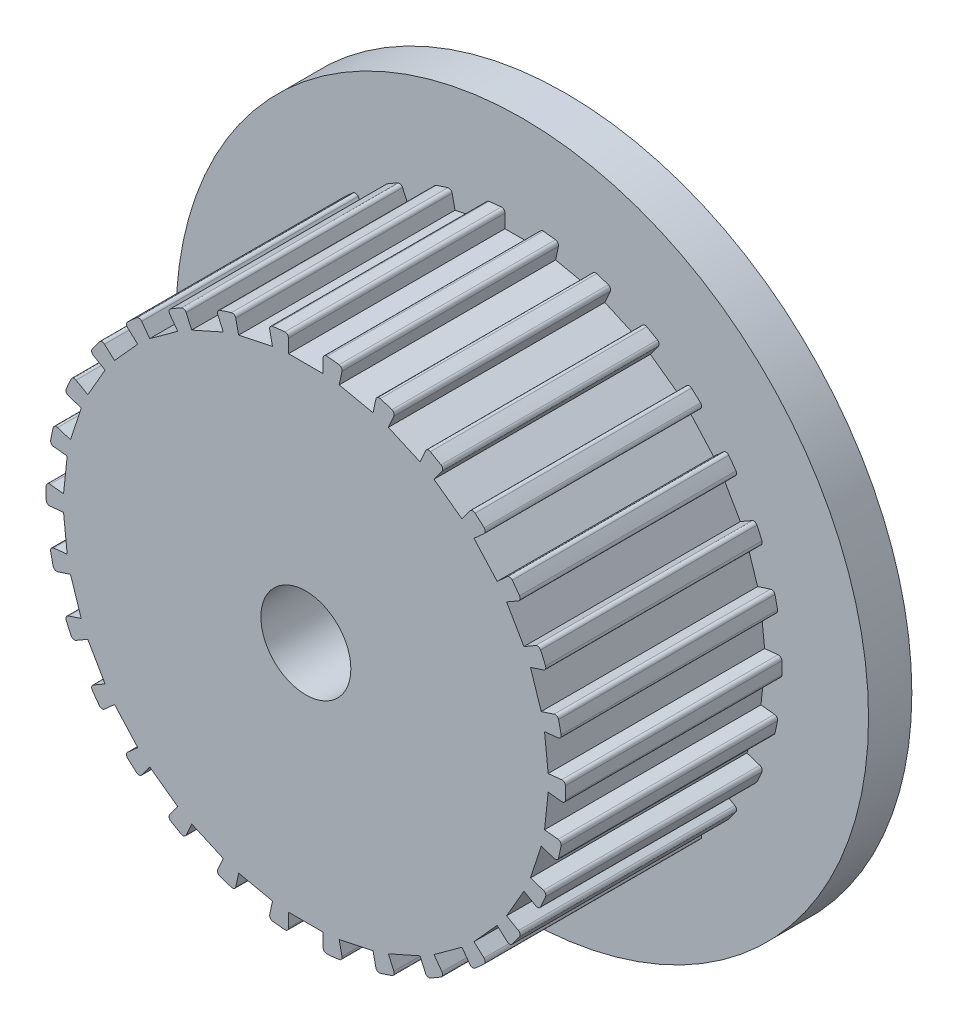
SolidWorks part; units mm, degrees
ref_plane "Front Plane" through (0, 0, 0) normal (0, 0, 1) x (1, 0, 0)
ref_plane "Top Plane" through (0, 0, 0) normal (0, 1, 0) x (1, 0, 0)
ref_plane "Right Plane" through (0, 0, 0) normal (1, 0, 0) x (0, 0, -1)
sketch "Sketch1" plane through (0, 0, 0) normal (0, 0, 1) x (1, 0, 0)
  circle A0 centre (0, 0) radius 12.7
  dimension "D1" = 25.4
extrude "Boss-Extrude1" add sketch "Sketch1" along normal blind 1.5875
sketch "Sketch2" plane through (0, 0, 1.5875) normal (0, 0, 1) x (1, 0, 0)
  circle A0 centre (0, 0) radius 9.525
  dimension "D1" = 19.05
extrude "Boss-Extrude2" add sketch "Sketch2" along normal blind 7.9375
sketch "Sketch3" plane through (0, 0, 9.525) normal (0, 0, 1) x (1, 0, 0)
  circle A0 centre (0, 0) radius 1.65
  dimension "D1" = 3.3
extrude "Cut-Extrude1" cut sketch "Sketch3" against normal through all
sketch "Sketch4" plane through (0, 0, 9.525) normal (0, 0, 1) x (1, 0, 0)
  line L0 (0, 8.8688) -> (0, 9.525) construction
  line L6 (-0.635, 9.5038) -> (0.635, 9.5038)
  line L7 (-0.635, 9.5038) -> (-0.635, 10.1388)
  line L8 (-0.635, 10.1388) -> (0.635, 10.1388)
  line L9 (0.635, 9.5038) -> (0.635, 10.1388)
  line L10 (-0.635, 9.5038) -> (0.635, 9.5038)
  line L11 (-0.635, 9.5038) -> (-0.635, 8.8688)
  line L12 (-0.635, 8.8688) -> (0.635, 8.8688)
  line L13 (0.635, 9.5038) -> (0.635, 8.8688)
  circle A0 centre (0, 0) radius 9.525 construction
  circle A5 centre (0, 0) radius 9.525 construction
  point P13 (0, 9.4966)
  dimension "D1" = 1.27
  dimension "D2" = 0.635
  dimension "D4" = 0.635
extrude "Cut-Extrude2" cut sketch "Sketch4" against normal up to surface (7.9375 mm away) contours L12 L13 L10 L11 | L7 L6 L9 L8 up to face at (9.525, 0, 1.5875)
fillet "Fillet2" radius 0.127 2 edges at (0.635, 9.5038, 5.5563) (-0.635, 9.5038, 5.5563)
pattern_circular "CirPattern1" count 30 over 360 about axis through (0, 0, 0) along (0, 0, 1) of "Cut-Extrude2", "Fillet2"
